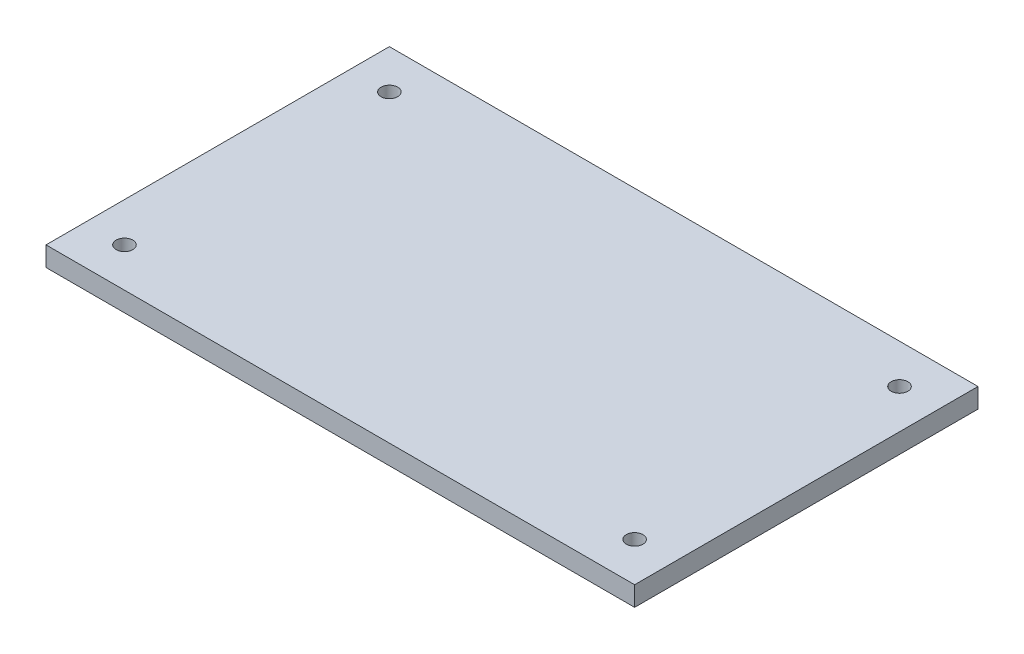
SolidWorks part; units mm, degrees
ref_plane "Front Plane" through (0, 0, 0) normal (0, 0, 1) x (1, 0, 0)
ref_plane "Top Plane" through (0, 0, 0) normal (0, 1, 0) x (1, 0, 0)
ref_plane "Right Plane" through (0, 0, 0) normal (1, 0, 0) x (0, 0, -1)
sketch "Sketch1" plane through (0, 0, 0) normal (0, 1, 0) x (1, 0, 0)
  line L0 (112, 8) -> (120, 8) construction
  line L1 (0, 0) -> (120, 0)
  line L2 (0, 0) -> (0, 70)
  line L3 (0, 70) -> (120, 70)
  line L4 (120, 0) -> (120, 70)
  line L5 (8, 70) -> (8, 62) construction
  line L6 (8, 62) -> (0, 62) construction
  line L7 (112, 8) -> (112, 0) construction
  line L8 (112, 70) -> (112, 62) construction
  line L9 (112, 62) -> (120, 62) construction
  line L10 (8, 8) -> (8, 0) construction
  line L11 (8, 8) -> (0, 8) construction
  circle A0 centre (8, 62) radius 1.7
  circle A4 centre (112, 62) radius 1.7
  circle A5 centre (112, 8) radius 1.7
  circle A6 centre (8, 8) radius 1.7
  dimension "D3" = 3.4
  dimension "D4" = 8
  dimension "D1" = 120
  dimension "D2" = 70
extrude "Boss-Extrude1" add sketch "Sketch1" along normal blind 4
equation "\"width\"= 120"
equation "\"depth\"= 70"
equation "\"hole_diameter\"= 3.4"
equation "\"hole_margin\"= 8"
equation "\"height\"= 4"
